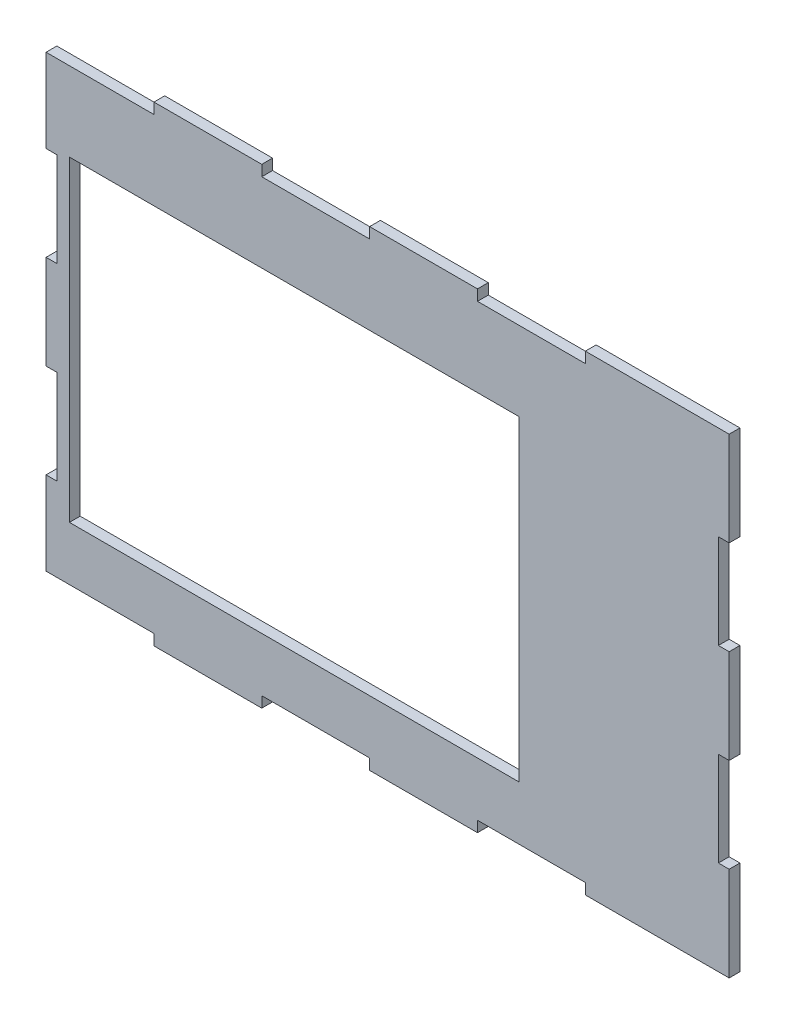
SolidWorks part; units mm, degrees
material "Acrylic (Medium-high impact)"
ref_plane "Front Plane" through (0, 0, 0) normal (0, 0, 1) x (1, 0, 0)
ref_plane "Top Plane" through (0, 0, 0) normal (0, 1, 0) x (1, 0, 0)
ref_plane "Right Plane" through (0, 0, 0) normal (1, 0, 0) x (0, 0, -1)
sketch "Sketch1" plane through (0, 0, 0) normal (0, 0, 1) x (1, 0, 0)
  line L253 (6.5, 106) -> (131.5, 106)
  line L254 (60, 131) -> (90, 131)
  line L255 (0, 0) -> (190, 0)
  line L256 (0, 0) -> (0, 131)
  line L257 (0, 131) -> (190, 131)
  line L258 (190, 0) -> (190, 131)
  line L259 (0, 131) -> (30, 131)
  line L260 (0, 131) -> (0, 128)
  line L261 (0, 128) -> (30, 128)
  line L262 (30, 131) -> (30, 128)
  line L263 (60, 131) -> (60, 128)
  line L264 (60, 128) -> (90, 128)
  line L265 (90, 131) -> (90, 128)
  line L266 (120, 131) -> (150, 131)
  line L267 (120, 131) -> (120, 128)
  line L268 (120, 128) -> (150, 128)
  line L269 (150, 131) -> (150, 128)
  line L270 (60, 3) -> (90, 3)
  line L271 (60, 3) -> (60, 0)
  line L272 (60, 0) -> (90, 0)
  line L273 (90, 3) -> (90, 0)
  line L274 (120, 3) -> (150, 3)
  line L275 (120, 3) -> (120, 0)
  line L276 (120, 0) -> (150, 0)
  line L277 (150, 3) -> (150, 0)
  line L278 (0, 3) -> (30, 3)
  line L279 (0, 3) -> (0, 0)
  line L280 (0, 0) -> (30, 0)
  line L281 (30, 3) -> (30, 0)
  line L282 (187, 104.8) -> (187, 78.6)
  line L283 (0, 104.8) -> (3, 104.8)
  line L284 (0, 104.8) -> (0, 78.6)
  line L285 (0, 78.6) -> (3, 78.6)
  line L286 (3, 104.8) -> (3, 78.6)
  line L287 (187, 104.8) -> (190, 104.8)
  line L288 (190, 104.8) -> (190, 78.6)
  line L289 (187, 78.6) -> (190, 78.6)
  line L290 (187, 52.4) -> (187, 26.2)
  line L291 (187, 52.4) -> (190, 52.4)
  line L292 (190, 52.4) -> (190, 26.2)
  line L293 (187, 26.2) -> (190, 26.2)
  line L294 (0, 52.4) -> (0, 26.2)
  line L295 (0, 52.4) -> (3, 52.4)
  line L296 (3, 52.4) -> (3, 26.2)
  line L297 (0, 26.2) -> (3, 26.2)
  line L298 (6.5, 106) -> (6.5, 18)
  line L299 (6.5, 18) -> (131.5, 18)
  line L300 (131.5, 106) -> (131.5, 18)
  dimension "D1" = 190
  dimension "D2" = 131
  dimension "D3" = 3
  dimension "D4" = 30
  dimension "D7" = 26.2
  dimension "D8" = 2
  dimension "D5" = 3
  dimension "D6" = 26.2
  dimension "D10" = 125
  dimension "D11" = 88
  dimension "D12" = 6.5
  dimension "D13" = 18
  dimension "D9" = 2
extrude "Boss-Extrude1" add sketch "Sketch1" along normal blind 3 contours L297 L256 L278 L281 L255 L271 L270 L273 L275 L274 L277 L258 L293 L290 L291 L289 L282 L287 L257 L269 L268 L267 L265 L264 L263 L262 L261 L283 L286 L285 L295 L296
